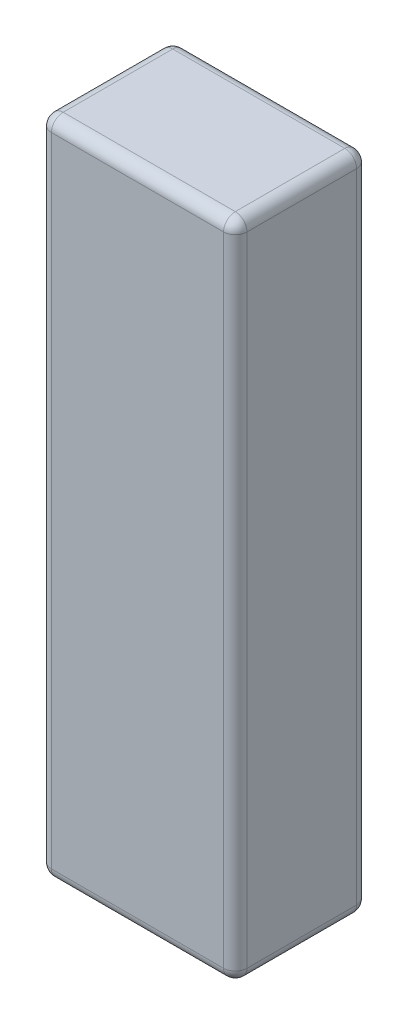
SolidWorks part; units mm, degrees
ref_plane "Front Plane" through (0, 0, 0) normal (0, 0, 1) x (1, 0, 0)
ref_plane "Top Plane" through (0, 0, 0) normal (0, 1, 0) x (1, 0, 0)
ref_plane "Right Plane" through (0, 0, 0) normal (1, 0, 0) x (0, 0, -1)
sketch "Sketch1" plane through (0, 0, 0) normal (0, 0, 1) x (1, 0, 0)
  line L1 (-25, -84.5) -> (25, -84.5)
  line L2 (-25, -84.5) -> (-25, 84.5)
  line L3 (-25, 84.5) -> (25, 84.5)
  line L4 (25, -84.5) -> (25, 84.5)
  line L5 (-25, -84.5) -> (25, 84.5) construction
  line L6 (-25, 84.5) -> (25, -84.5) construction
  point P0 (0, 0)
  dimension "D1" = 50
  dimension "D2" = 169
extrude "Boss-Extrude1" add sketch "Sketch1" along normal mid plane 34
sketch "Sketch2" plane through (0, 0, 0) normal (1, 0, 0) x (0, 0, -1)
  line L0 (-17, 84.5) -> (17, -84.5) construction
fillet "Fillet1" radius 3 12 edges at (-25, 0, 17) (-25, 0, -17) (25, 0, 17) (25, 0, -17) (-25, -84.5, 0) (0, -84.5, 17) (25, -84.5, 0) (0, -84.5, -17) (25, 84.5, 0) (0, 84.5, 17) (-25, 84.5, 0) (0, 84.5, -17)
